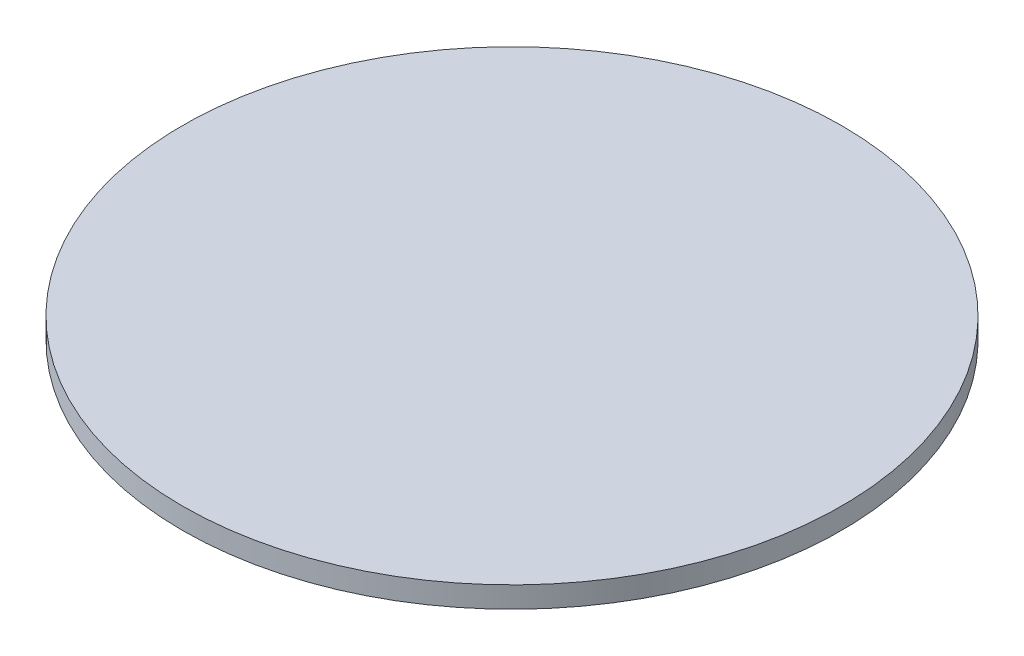
SolidWorks part; units mm, degrees
material "G10 Fiberglass Sheet"
ref_plane "Front Plane" through (0, 0, 0) normal (0, 0, 1) x (1, 0, 0)
ref_plane "Top Plane" through (0, 0, 0) normal (0, 1, 0) x (1, 0, 0)
ref_plane "Right Plane" through (0, 0, 0) normal (1, 0, 0) x (0, 0, -1)
sketch "Sketch2" plane through (0, 0, 0) normal (0, 1, 0) x (1, 0, 0)
  circle A0 centre (0, 0) radius 49.53
  dimension "D1" = 99.06
extrude "Boss-Extrude1" add sketch "Sketch2" along normal blind 3.175 contours A0
